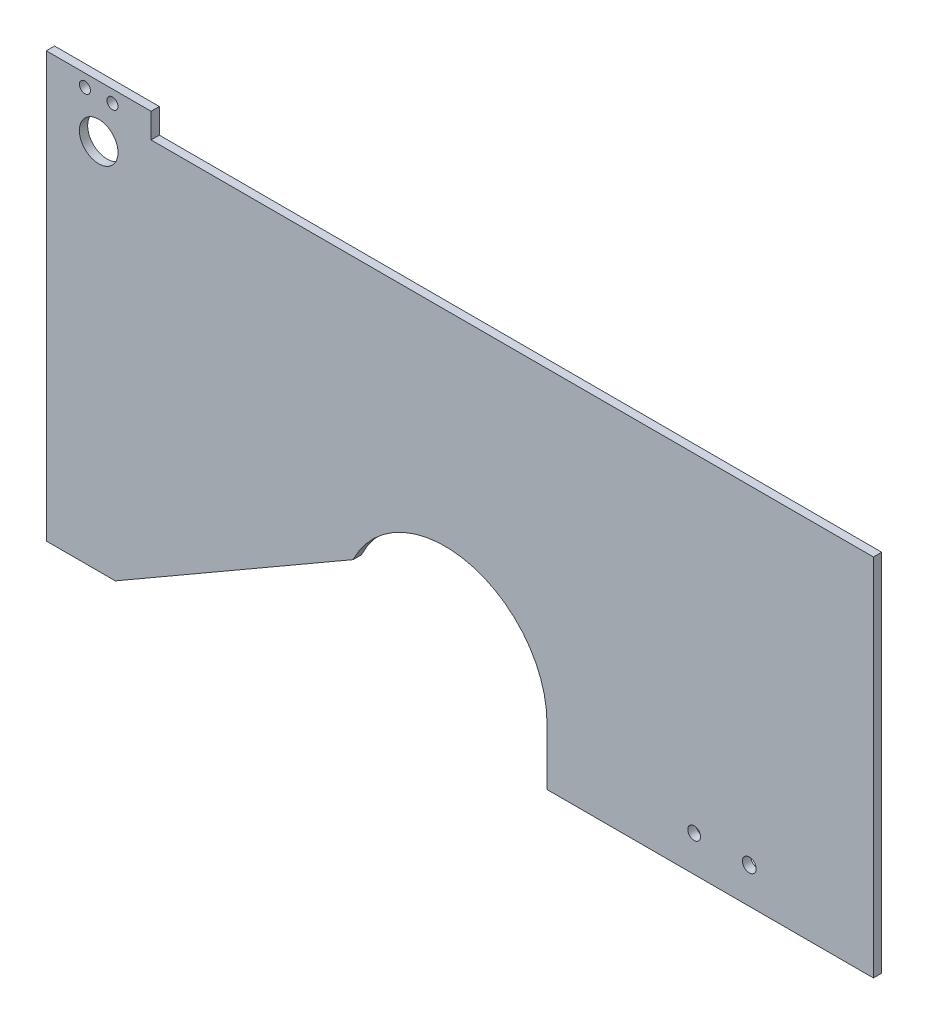
SolidWorks part; units mm, degrees
ref_plane "Front Plane" through (0, 0, 0) normal (0, 0, 1) x (1, 0, 0)
ref_plane "Top Plane" through (0, 0, 0) normal (0, 1, 0) x (1, 0, 0)
ref_plane "Right Plane" through (0, 0, 0) normal (1, 0, 0) x (0, 0, -1)
sketch "Sketch2" plane through (0, 0, 0) normal (0, 0, 1) x (1, 0, 0)
  line L0 (25.0304, 0) -> (111.2865, 49.8)
  line L1 (0, 0) -> (25.0304, 0)
  line L2 (0, 0) -> (0, 154)
  line L4 (300, 0) -> (300, 145)
  line L5 (181.6, 33.7) -> (181.6, 0)
  line L6 (181.6, 0) -> (300, 0)
  line L7 (19, 135) -> (19, 164.3674) construction
  line L11 (38, 145) -> (300, 145)
  line L12 (0, 154) -> (19, 154)
  line L13 (19, 154) -> (38, 154)
  line L14 (38, 154) -> (38, 145)
  line L15 (19, 135) -> (50019, 135) construction
  line L20 (19, 135) -> (19, -49865) construction
  circle A0 centre (19, 135) radius 7
  arc A1 (181.6, 33.7) -> (111.2865, 49.8) centre (144.6, 33.7) ccw
  circle A2 centre (14, 149.5) radius 2
  circle A3 centre (24, 149.5) radius 2
  point P19 (19, 154)
  dimension "D3" = 135
  dimension "D4" = 19
  dimension "D5" = 14
  dimension "D6" = 74
  dimension "D7" = 155.4
  dimension "D8" = 33.7
  dimension "D13" = 4
  dimension "D14" = 5
  dimension "D15" = 14.5
  dimension "D1" = 300
  dimension "D2" = 154
  dimension "D9" = 30
  dimension "D10" = 99.6
  dimension "D11" = 19
  dimension "D12" = 145
  dimension "D16" = 9
extrude "Boss-Extrude2" add sketch "Sketch2" along normal blind 3
sketch "Sketch3" plane through (0, 0, 3) normal (0, 0, 1) x (1, 0, 0)
  line L0 (300, 0) -> (300, 145) construction
  line L1 (181.6, 0) -> (300, 0)
  line L2 (181.6, 0) -> (181.6, 12.75)
  line L3 (181.6, 12.75) -> (300, 12.75)
  line L4 (300, 0) -> (300, 12.75)
  dimension "D1" = 12.75
extrude "Cut-Extrude1" cut sketch "Sketch3" against normal through all
sketch "Sketch4" plane through (0, 0, 3) normal (0, 0, 1) x (1, 0, 0)
  line L0 (19, 135) -> (19, -49865) construction
  line L1 (19, 135) -> (-49981, 135) construction
sketch "Sketch5" plane through (0, 0, 3) normal (0, 0, 1) x (1, 0, 0)
  line L0 (300, 12.75) -> (300, 145) construction
  line L1 (300, 12.75) -> (181.6, 12.75) construction
  circle A0 centre (254.98, 25.75) radius 2.5
  circle A1 centre (234.98, 25.75) radius 2.3061
  dimension "D1" = 45.02
  dimension "D2" = 13
  dimension "D3" = 20
  dimension "D4" = 13
  dimension "D5" = 4.6121
  dimension "D6" = 5
extrude "Cut-Extrude2" cut sketch "Sketch5" against normal through all
